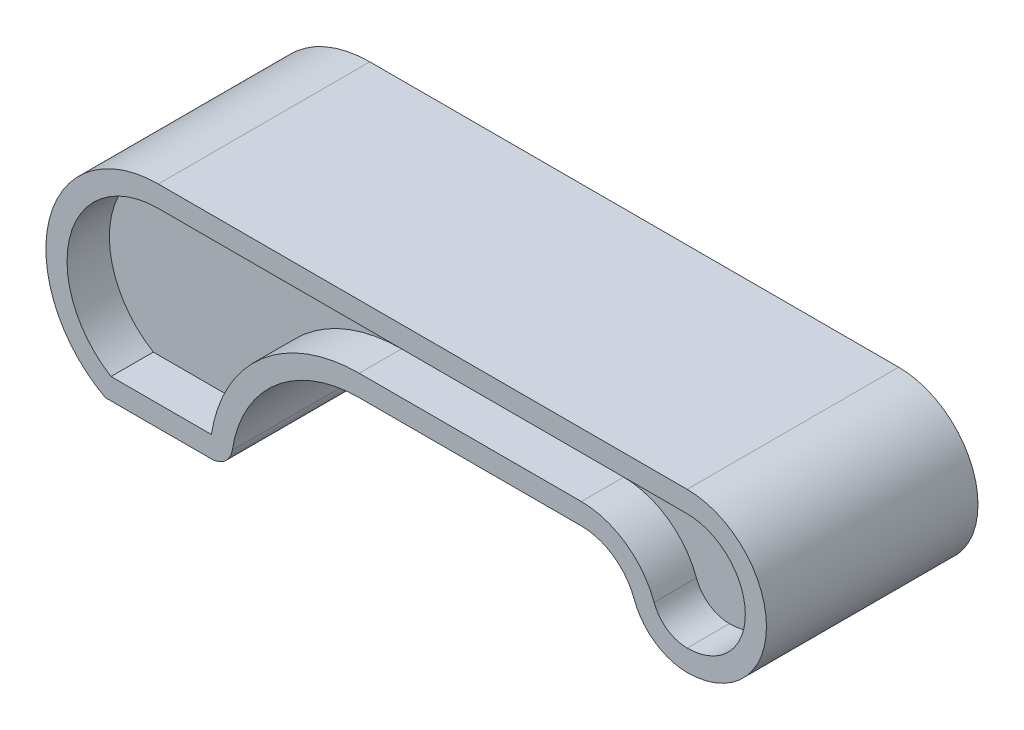
SolidWorks part; units mm, degrees
ref_plane "Front Plane" through (0, 0, 0) normal (0, 0, 1) x (1, 0, 0)
ref_plane "Top Plane" through (0, 0, 0) normal (0, 1, 0) x (1, 0, 0)
ref_plane "Right Plane" through (0, 0, 0) normal (1, 0, 0) x (0, 0, -1)
sketch "Sketch1" plane through (0, 0, 0) normal (0, 0, 1) x (1, 0, 0)
  line L0 (0, 0) -> (10, 0)
  line L1 (5, 20) -> (55, 20)
  line L2 (45, 12) -> (24, 12)
  line L3 (55, 20) -> (55, 5) construction
  arc A0 (0, 0) -> (5, 20) centre (5, 9.375) cw
  arc A1 (55, 20) -> (55, 5) centre (55, 12.5) cw
  arc A2 (55, 5) -> (50, 8.5) centre (55, 10.3214) cw
  arc A3 (50, 8.5) -> (45, 12) centre (45, 6.6786) ccw
  arc A5 (10, 0) -> (12, 1.7143) centre (10, 2.0238) ccw
  arc A6 (12, 1.7143) -> (24, 12) centre (24, -0.1429) cw
  dimension "D4" = 50
  dimension "D1" = 10
  dimension "D2" = 20
  dimension "D3" = 15
  dimension "D5" = 8
  dimension "D6" = 5
  dimension "D7" = 2
  dimension "D8" = 12
  dimension "D9" = 5
extrude "Boss-Extrude1" add sketch "Sketch1" along normal blind 20 contours A6 L2 A3 A2 A1 L1 A0 L0 A5
ref_plane "Plane1" through (0, 0, 10) normal (0, 0, 1) x (1, 0, 0)
sketch "Sketch3" plane through (0, 0, 20) normal (0, 0, 1) x (1, 0, 0)
  line L6 (24, 14) -> (45, 14)
  line L7 (55, 18) -> (5, 18)
  line L8 (0.5279, 2) -> (10, 2)
  line L9 (24, 14) -> (45, 14)
  line L10 (55, 18) -> (5, 18)
  line L11 (0.5279, 2) -> (10, 2)
  arc A12 (10, 2) -> (10.0235, 2.0202) centre (10, 2.0238) ccw
  arc A13 (24, 14) -> (10.0235, 2.0202) centre (24, -0.1429) ccw
  arc A14 (51.8792, 9.1846) -> (45, 14) centre (45, 6.6786) ccw
  arc A15 (51.8792, 9.1846) -> (55, 7) centre (55, 10.3214) ccw
  arc A16 (55, 7) -> (55, 18) centre (55, 12.5) ccw
  arc A17 (5, 18) -> (0.5279, 2) centre (5, 9.375) ccw
  arc A18 (10, 2) -> (10.0235, 2.0202) centre (10, 2.0238) ccw
  arc A19 (24, 14) -> (10.0235, 2.0202) centre (24, -0.1429) ccw
  arc A20 (51.8792, 9.1846) -> (45, 14) centre (45, 6.6786) ccw
  arc A21 (51.8792, 9.1846) -> (55, 7) centre (55, 10.3214) ccw
  arc A22 (55, 7) -> (55, 18) centre (55, 12.5) ccw
  arc A23 (5, 18) -> (0.5279, 2) centre (5, 9.375) ccw
  dimension "D1" = 2
extrude "Cut-Extrude1" cut sketch "Sketch3" against normal blind 4
mirror "Mirror1" about plane through (0, 0, 10) normal (0, 0, 1) of "Cut-Extrude1"
sketch "Sketch4" plane through (0, 0, 0) normal (0, -1, 0) x (-1, 0, 0)
  line L0 (0, 0) -> (-10, -20) construction
  circle A0 centre (-5, -10) radius 4
  dimension "D1" = 8
extrude "Cut-Extrude2" cut sketch "Sketch4" against normal blind 2
